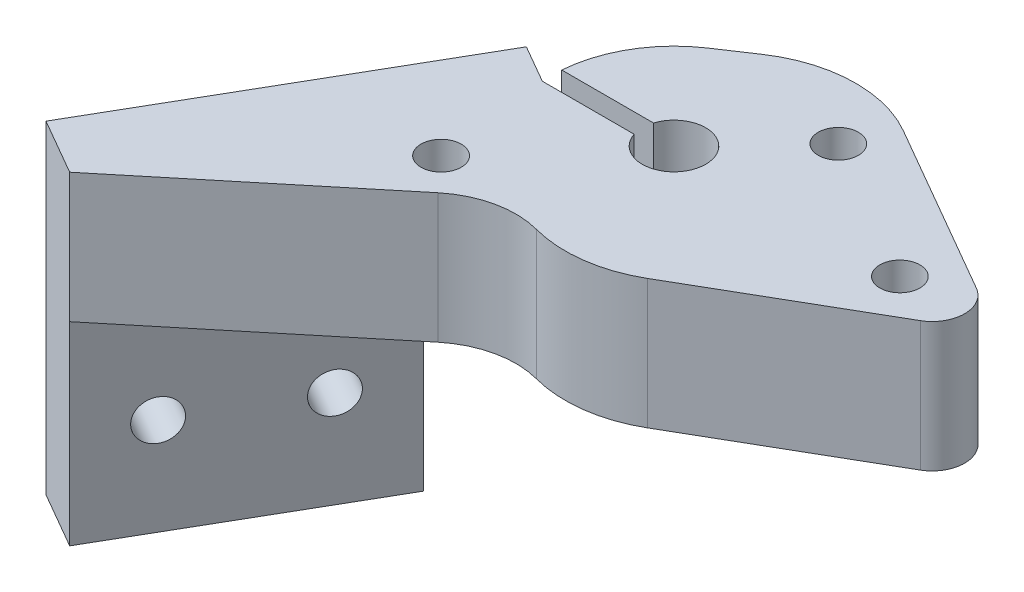
SolidWorks part; units mm, degrees
ref_plane "Front Plane" through (0, 0, 0) normal (0, 0, 1) x (1, 0, 0)
ref_plane "Top Plane" through (0, 0, 0) normal (0, 1, 0) x (1, 0, 0)
ref_plane "Right Plane" through (0, 0, 0) normal (1, 0, 0) x (0, 0, -1)
sketch "Sketch1" plane through (0, 0, 0) normal (0, 1, 0) x (1, 0, 0)
  line L0 (-7.5, -12.9904) -> (-3.75, -6.4952) construction
  line L1 (11.25, 2.1651) -> (-2.1212, 9.8849)
  line L2 (-7.5, 12.9904) -> (-7.5, -12.9904) construction
  line L3 (-2.1212, -9.8849) -> (11.25, -2.1651)
  line L4 (-7.5, 12.9904) -> (-3.75, 6.4952) construction
  line L5 (0, 0) -> (-7.5, 0) construction
  line L7 (-12.6679, -9.5454) -> (-15.1916, -7.8631)
  line L8 (-12.6679, 9.5454) -> (-15.1916, 7.8631)
  circle A0 centre (0, 0) radius 7.5 construction
  circle A1 centre (7.5, 0) radius 1.55
  circle A2 centre (-3.75, -6.4952) radius 1.55 construction
  circle A3 centre (-3.75, 6.4952) radius 1.55
  circle A4 centre (-9.95, 0) radius 2.45
  arc A5 (-15.1916, 7.8631) -> (-15.1916, -7.8631) centre (-9.95, 0) ccw
  arc A6 (-12.6679, -9.5454) -> (-2.1212, -9.8849) centre (-7.1212, -1.2247) ccw
  arc A7 (-2.1212, 9.8849) -> (-12.6679, 9.5454) centre (-7.1212, 1.2247) ccw
  arc A8 (11.25, 2.1651) -> (11.25, -2.1651) centre (10, 0) cw
  dimension "D2" = 3.1
  dimension "D3" = 4.9
  dimension "D4" = 7
  dimension "D5" = 10
  dimension "D6" = 2.5
  dimension "D1" = 7.5
extrude "Boss-Extrude1" add sketch "Sketch1" along normal blind 10
sketch "Sketch2" plane through (0, 10, 0) normal (0, 1, 0) x (1, 0, 0)
  line L0 (-9.95, 0.75) -> (-9.95, -0.75)
  line L1 (-9.95, 0.75) -> (-19.4, 0.75)
  line L2 (-9.95, -0.75) -> (-19.4, -0.75)
  line L3 (-19.4, 0.75) -> (-19.4, -0.75)
  arc A0 (-15.1916, 7.8631) -> (-15.1916, -7.8631) centre (-9.95, 0) ccw construction
  point P0 (-9.95, 0)
  dimension "D1" = 1.5
extrude "Cut-Extrude1" cut sketch "Sketch2" against normal through all
sketch "Sketch3" plane through (0, 0, 0) normal (0, -1, 0) x (1, 0, 0)
  line L0 (-22.286, -0.9334) -> (-35.8687, 22.5925)
  line L1 (-35.8687, 22.5925) -> (-31.5386, 25.0925)
  line L2 (-31.5386, 25.0925) -> (-12.6679, 9.5454)
  line L3 (7.5, 0) -> (-3.75, -6.4952) construction
  line L4 (-19.3702, 0.75) -> (-22.286, -0.9334)
  line L6 (-12.6679, 9.5454) -> (-24.4189, 2.7609) construction
  dimension "D1" = 3.3669
  dimension "D2" = 22.8995
  dimension "D3" = 5
extrude "Boss-Extrude3" add sketch "Sketch3" against normal up to surface (10 mm away) up to face at (-8.0388, 10, 0)
sketch "Sketch4" plane through (0, 0, 0) normal (0, 1, 0) x (1, 0, 0)
  line L0 (-35.8687, -22.5925) -> (-25.8687, -5.272)
  line L1 (-35.8687, -22.5925) -> (-31.5386, -25.0925)
  line L2 (-25.8687, -5.272) -> (-21.5386, -7.772)
  line L3 (-31.5386, -25.0925) -> (-21.5386, -7.772)
  line L4 (-22.286, 0.9334) -> (-35.8687, -22.5925) construction
  dimension "D1" = 20
  dimension "D2" = 5
extrude "Boss-Extrude4" add sketch "Sketch4" against normal blind 15
hole_wizard "Ø3.0mm Clearance Dowel Hole2" positions "Sketch6" profile "Sketch5" hole size "Ø3.0" standard "DIN" end condition through all
sketch "Sketch6" plane through (-12.7886, 0, -7.3835) normal (0.866, 0, 0.5) x (0.5, 0, -0.866)
  line L7 (-27.5, -15) -> (-27.5, 0) construction
  line L8 (-37.5, -15) -> (-17.5, -15) construction
  line L9 (-37.5, 0) -> (-17.5, 0) construction
  point P13 (-22.5, -7.5)
  point P70 (-32.5, -7.5)
  dimension "D1" = 5
  dimension "D2" = 7.5
  dimension "D3" = 5
  dimension "D4" = 7.5
sketch "Sketch5" plane through (-24.0386, -7.5, 12.1021) normal (0, 1, 0) x (0.5, 0, -0.866)
  line L0 (0, 0) -> (0, 21.9086)
  line L1 (0, 21.9086) -> (1.554, 21.9086)
  line L2 (1.554, 21.9086) -> (1.554, 0)
  line L5 (1.554, 0) -> (0, 0)
  line L11 (0, -6.35) -> (0, 107.95) construction
  dimension "Thru Hole Dia." = 3.108
  dimension "Thru Hole Depth" = 21.9086
hole_wizard "Ø3.0mm Clearance Dowel Hole3" positions "Sketch8" profile "Sketch7" hole size "Ø3.0" standard "DIN" end condition through all
sketch "Sketch8" plane through (0, 0, 0) normal (0, -1, 0) x (-1, 0, 0)
  line L0 (21.5386, -7.772) -> (15.0573, -11.5139) construction
  line L1 (31.5386, -25.0925) -> (12.6679, -9.5454) construction
  line L3 (21.5386, -7.772) -> (25.8687, -5.272) construction
  point P0 (18.2979, -9.643)
sketch "Sketch7" plane through (-18.2979, 0, 9.643) normal (1, 0, 0) x (0, 0, -1)
  line L0 (0, 0) -> (0, 10)
  line L1 (0, 10) -> (1.554, 10)
  line L2 (1.554, 10) -> (1.554, 0)
  line L5 (1.554, 0) -> (0, 0)
  line L11 (0, -6.35) -> (0, 107.95) construction
  dimension "Thru Hole Dia." = 3.108
  dimension "Thru Hole Depth" = 10
fillet "Fillet2" radius 7 1 edges at (-12.6679, 5, 9.5454)
